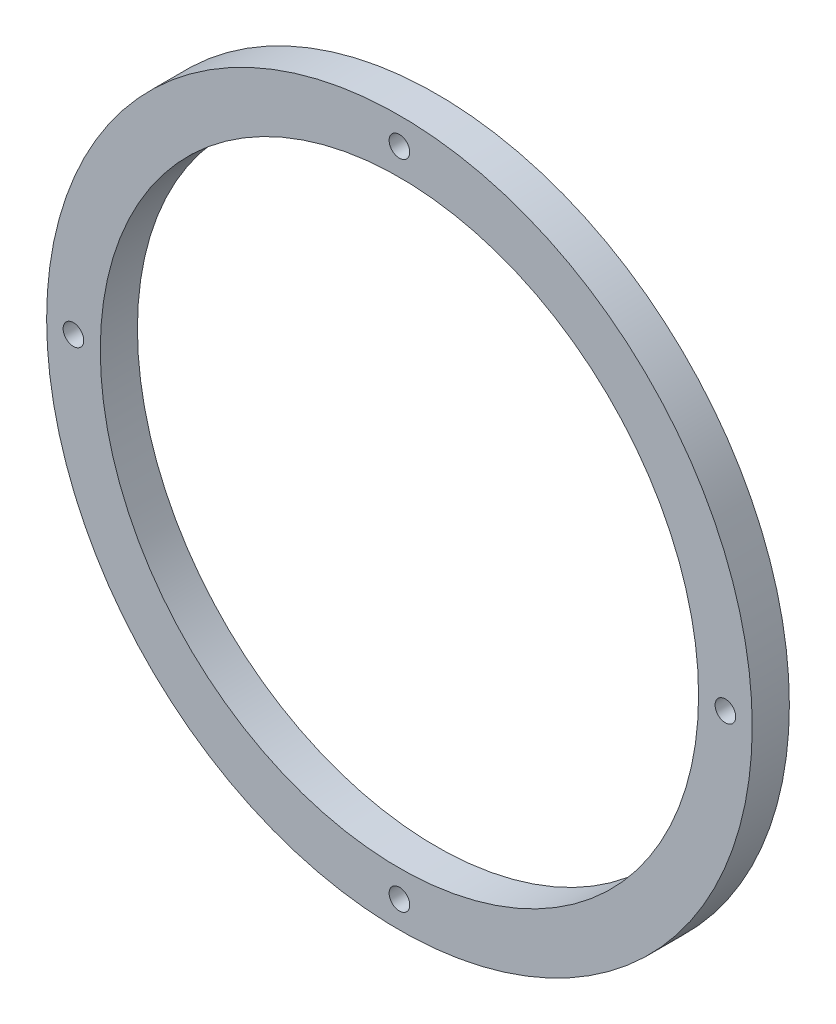
SolidWorks part; units mm, degrees
material "1060 合金"
ref_plane "前视基准面" through (0, 0, 0) normal (0, 0, 1) x (1, 0, 0)
ref_plane "上视基准面" through (0, 0, 0) normal (0, 1, 0) x (1, 0, 0)
ref_plane "右视基准面" through (0, 0, 0) normal (1, 0, 0) x (0, 0, -1)
sketch "草图1" plane through (0, 0, 0) normal (0, 0, 1) x (1, 0, 0)
  circle A0 centre (0, 0) radius 72.5
  circle A1 centre (0, 0) radius 85.5
  dimension "D1" = 145
  dimension "D2" = 171
extrude "凸台-拉伸1" add sketch "草图1" along normal blind 9
sketch "草图3" plane through (0, 0, 9) normal (0, 0, 1) x (1, 0, 0)
  line L0 (0, 79) -> (0, 0) construction
  circle A0 centre (0, 79) radius 2.5
  circle A1 centre (79, 0) radius 2.5
  circle A2 centre (0, -79) radius 2.5
  circle A3 centre (-79, 0) radius 2.5
  dimension "D2" = 5
  dimension "D1" = 79
  dimension "D3" = 4
extrude "切除-拉伸1" cut sketch "草图3" against normal through all
